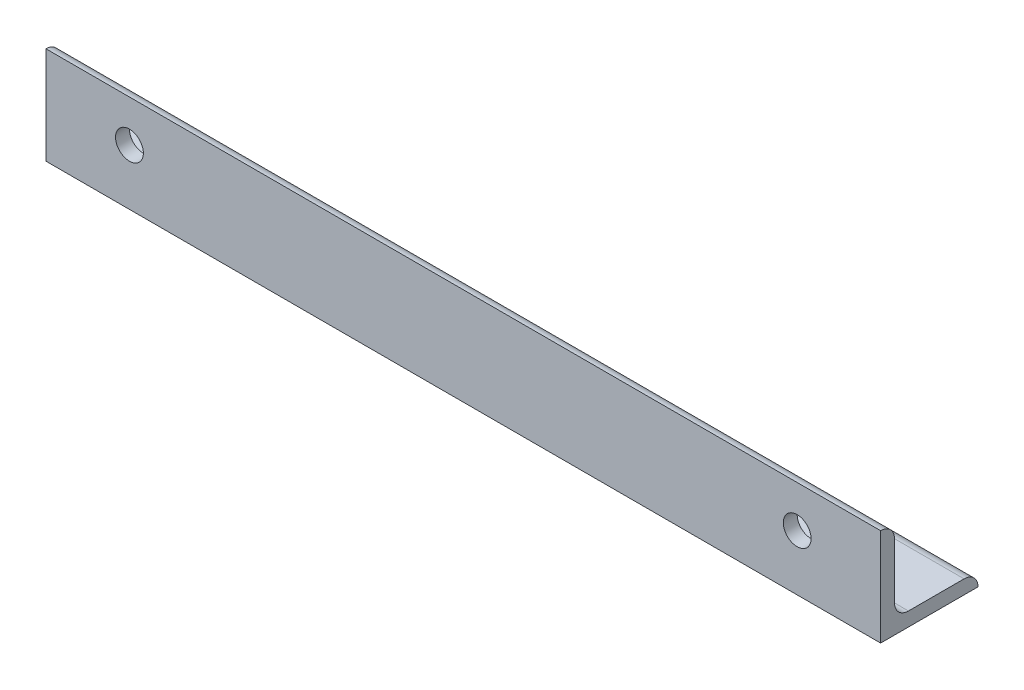
SolidWorks part; units mm, degrees
ref_plane "Płaszczyzna przednia" through (0, 0, 0) normal (0, 0, 1) x (1, 0, 0)
ref_plane "Płaszczyzna górna" through (0, 0, 0) normal (0, 1, 0) x (1, 0, 0)
ref_plane "Płaszczyzna prawa" through (0, 0, 0) normal (1, 0, 0) x (0, 0, -1)
sketch3d "Szkic 3D1"
  line L0 (0, 0, 0) -> (300, 0, 0)
  dimension "D1" = 300
other "Kątownik stalowy 35 X 35 X 5(1)"
ref_plane "Płaszczyzna1" through (0, 0, 0) normal (1, 0, 0) x (0, 0, -1)
sketch "Sketch1" plane through (0, 0, 0) normal (1, 0, 0) x (0, 0, -1)
  line L0 (0, 0) -> (0, 35)
  line L1 (0, 17.5) -> (5, 17.5) construction
  line L2 (5, 30) -> (5, 10)
  line L3 (10, 5) -> (30, 5)
  line L4 (17.5, 5) -> (17.5, 0) construction
  line L5 (35, 0) -> (0, 0)
  arc A0 (35, 0) -> (30, 5) centre (30, 0) ccw
  arc A1 (0, 35) -> (5, 30) centre (0, 30) cw
  arc A2 (10, 5) -> (5, 10) centre (10, 10) cw
  point P10 (17.5, 0)
  point P14 (0, 17.5)
  point P15 (5, 17.5)
  point P16 (17.5, 5)
  point P17 (5, 35)
  point P18 (35, 5)
  point P21 (0, 0)
  dimension "D2" = 5
  dimension "D3" = 35
  dimension "Radius_1" = 5
  dimension "D1" = 5
sketch "Szkic2" plane through (0, 0, -5) normal (0, 0, -1) x (-1, 0, 0)
  line L0 (-150, 69.0731) -> (-150, -74.3509) construction
  line L3 (-300, 35) -> (0, 35) construction
  circle A0 centre (-270, 20) radius 5
  circle A1 centre (-30, 20) radius 5
  dimension "D1" = 240
  dimension "D2" = 10
  dimension "D3" = 15
extrude "Wytnij-wyciągnięcie1" cut sketch "Szkic2" against normal through all
